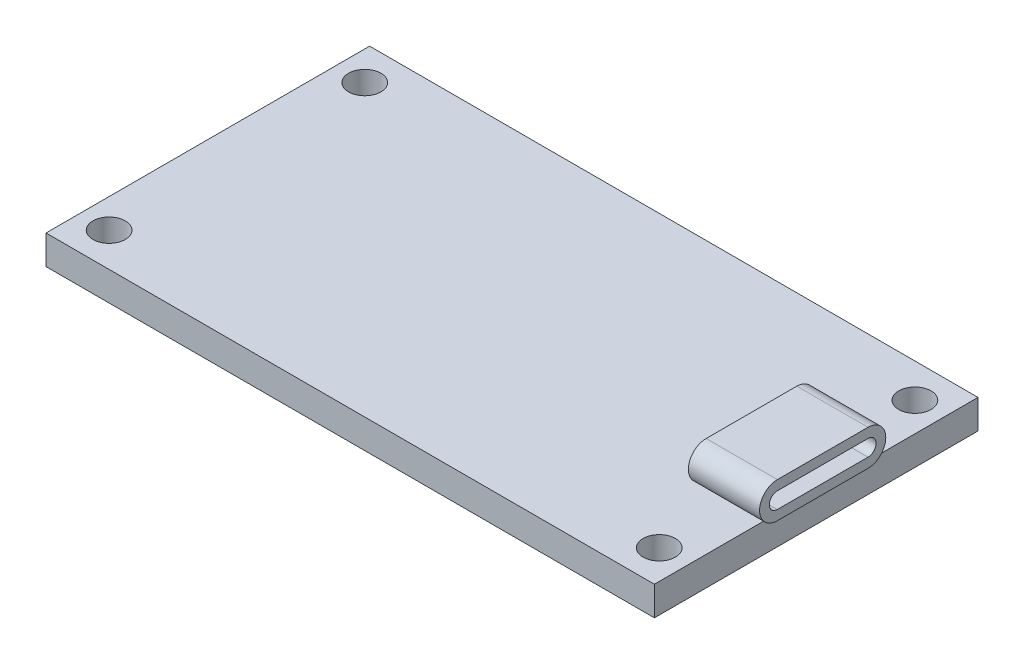
SolidWorks part; units mm, degrees
ref_plane "Front Plane" through (0, 0, 0) normal (0, 0, 1) x (1, 0, 0)
ref_plane "Top Plane" through (0, 0, 0) normal (0, 1, 0) x (1, 0, 0)
ref_plane "Right Plane" through (0, 0, 0) normal (1, 0, 0) x (0, 0, -1)
sketch "Sketch1" plane through (0, 0, 0) normal (0, 1, 0) x (1, 0, 0)
  line L0 (23.876, 0) -> (-23.876, 0) construction
  line L1 (-23.876, 12.7) -> (23.876, 12.7)
  line L2 (-23.876, 12.7) -> (-23.876, -12.7)
  line L3 (-23.876, -12.7) -> (23.876, -12.7)
  line L4 (23.876, 12.7) -> (23.876, -12.7)
  line L7 (0, -12.7) -> (0, 12.7) construction
  line L9 (-21.59, 10.033) -> (21.59, 10.033) construction
  line L10 (-21.59, 10.033) -> (-21.59, -10.033) construction
  line L11 (-21.59, -10.033) -> (21.59, -10.033) construction
  line L12 (21.59, 10.033) -> (21.59, -10.033) construction
  circle A0 centre (-21.59, 10.033) radius 1.27
  circle A1 centre (21.59, 10.033) radius 1.27
  circle A2 centre (-21.59, -10.033) radius 1.27
  circle A3 centre (21.59, -10.033) radius 1.27
  point P0 (0, 0)
  point P18 (0, 0)
  dimension "D3" = 2.54
  dimension "D4" = 43.18
  dimension "D1" = 47.752
  dimension "D2" = 25.4
  dimension "D5" = 20.066
extrude "Boss-Extrude1" add sketch "Sketch1" along normal blind 2.286
sketch "Sketch2" plane through (23.876, 0, 0) normal (1, 0, 0) x (0, 0, -1)
  line L0 (0, 0) -> (0, 4.4653) construction
  line L1 (-12.7, 0) -> (12.7, 0) construction
  line L3 (-3.556, 3.683) -> (3.556, 3.683) construction
  line L4 (-3.556, 3.683) -> (3.556, 3.683) construction
  line L5 (-3.556, 5.08) -> (3.556, 5.08)
  line L6 (-3.556, 2.286) -> (3.556, 2.286)
  line L7 (-12.7, 2.286) -> (12.7, 2.286) construction
  arc A0 (-3.556, 5.08) -> (-3.556, 2.286) centre (-3.556, 3.683) ccw
  arc A1 (3.556, 2.286) -> (3.556, 5.08) centre (3.556, 3.683) ccw
  point P4 (0, 3.683)
  dimension "D2" = 7.112
  dimension "D1" = 5.08
  dimension "D3" = 2.794
extrude "Boss-Extrude2" add sketch "Sketch2" along normal blind 0.508 and the other way blind 5.08
sketch "Sketch3" plane through (24.384, 0, 0) normal (1, 0, 0) x (0, 0, -1)
  line L0 (-3.556, 3.683) -> (3.556, 3.683) construction
  line L1 (-3.556, 4.318) -> (3.556, 4.318)
  line L2 (-3.556, 3.048) -> (3.556, 3.048)
  line L3 (-3.556, 2.286) -> (3.556, 2.286) construction
  line L4 (3.556, 5.08) -> (-3.556, 5.08) construction
  line L5 (-3.556, 2.286) -> (3.556, 2.286) construction
  line L6 (3.556, 5.08) -> (-3.556, 5.08) construction
  arc A0 (-3.556, 4.318) -> (-3.556, 3.048) centre (-3.556, 3.683) ccw
  arc A1 (3.556, 3.048) -> (3.556, 4.318) centre (3.556, 3.683) ccw
  arc A5 (-3.556, 5.08) -> (-3.556, 2.286) centre (-3.556, 3.683) ccw construction
  arc A6 (3.556, 2.286) -> (3.556, 5.08) centre (3.556, 3.683) ccw construction
  arc A7 (-3.556, 5.08) -> (-3.556, 2.286) centre (-3.556, 3.683) ccw construction
  arc A8 (3.556, 2.286) -> (3.556, 5.08) centre (3.556, 3.683) ccw construction
  point P2 (0, 3.683)
  point P7 (0, 0)
  point P11 (0, 0)
  point P12 (2.6337, 2.921)
  point P14 (0, 0)
  dimension "D1" = 0.635
extrude "Cut-Extrude1" cut sketch "Sketch3" against normal offset from surface (4.064 mm away) 1.524 up to face at (18.796, 3.683, 0)
